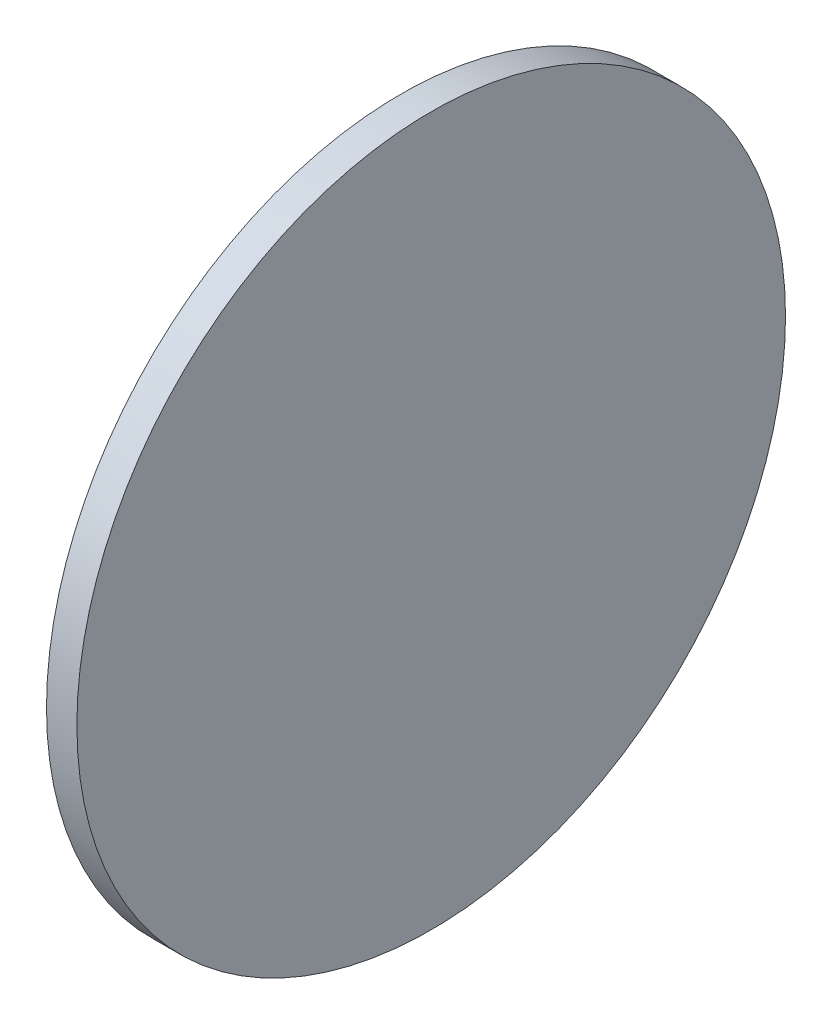
SolidWorks part; units mm, degrees
material "E-Glass Fiber"
ref_plane "Front Plane" through (0, 0, 0) normal (0, 0, 1) x (1, 0, 0)
ref_plane "Top Plane" through (0, 0, 0) normal (0, 1, 0) x (1, 0, 0)
ref_plane "Right Plane" through (0, 0, 0) normal (1, 0, 0) x (0, 0, -1)
sketch "Sketch1" plane through (0, 0, 0) normal (1, 0, 0) x (0, 0, -1)
  circle A0 centre (0, 0) radius 74.041
  dimension "D1" = 148.082
extrude "Boss-Extrude1" add sketch "Sketch1" along normal blind 6.35
